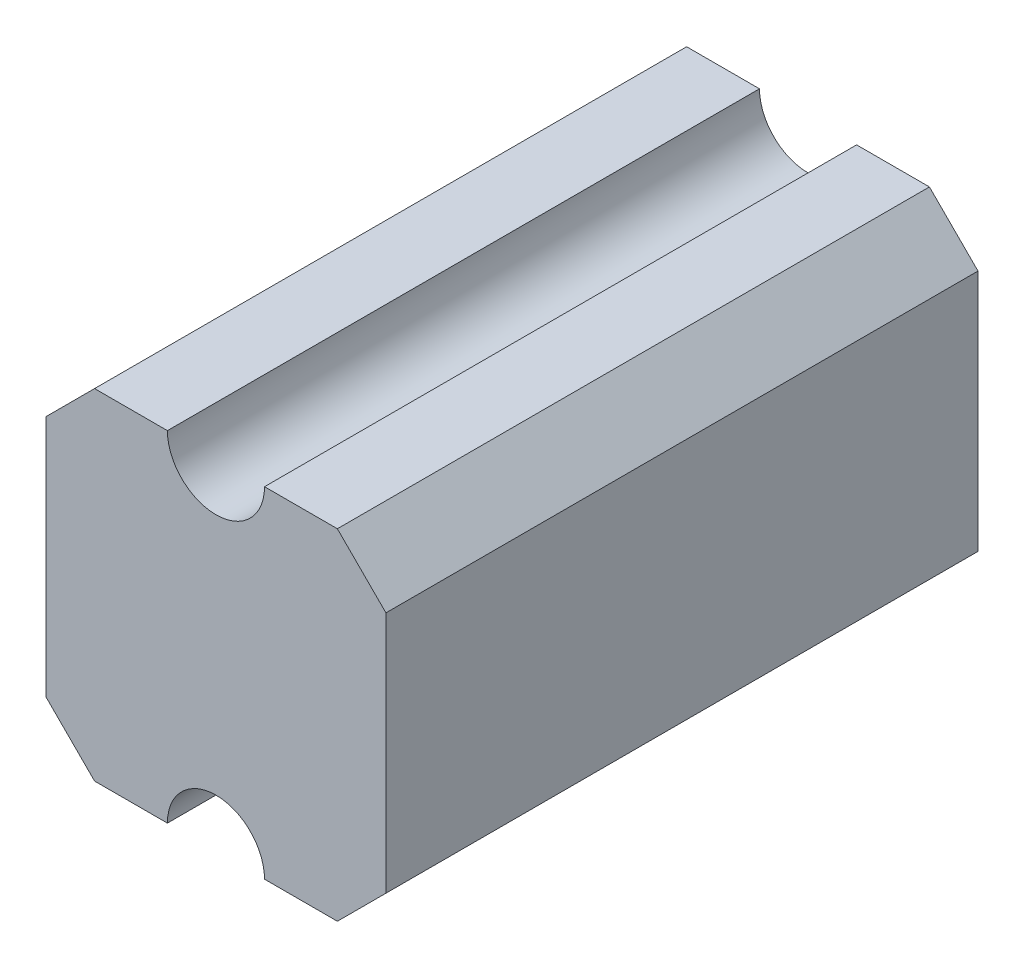
SolidWorks part; units mm, degrees
ref_plane "Front Plane" through (0, 0, 0) normal (0, 0, 1) x (1, 0, 0)
ref_plane "Top Plane" through (0, 0, 0) normal (0, 1, 0) x (1, 0, 0)
ref_plane "Right Plane" through (0, 0, 0) normal (1, 0, 0) x (0, 0, -1)
sketch3d "3DSketch1"
  line L2 (177.8, 103.1591, 1515.8003) -> (177.8, 458.7543, 1515.8003)
  line L3 (177.8, 458.7543, 1515.8003) -> (-177.8, 458.7543, 1515.8003)
  line L4 (-177.8, 458.7543, 1515.8003) -> (-177.8, 103.1591, 1515.8003)
  line L5 (-177.8, 103.1591, 1515.8003) -> (177.8, 103.1591, 1515.8003)
  line L8 (177.8, 50.7952, 937.9503) -> (234.95, 239.528, 988.7503)
  line L9 (234.95, 239.528, 988.7503) -> (234.95, 239.528, 753.8003)
  line L17 (-177.8, 50.7952, 937.9503) -> (-234.95, 239.528, 988.7503)
  line L18 (-234.95, 239.528, 988.7503) -> (-234.95, 239.528, 753.8003)
  line L26 (177.8, 50.7952, 753.8003) -> (304.8, 0, 0)
  line L27 (-177.8, 50.7952, 753.8003) -> (-304.8, 0, 0)
  line L29 (-234.95, 239.528, 753.8003) -> (-336.55, 241.3, -38.2182)
  line L32 (234.95, 239.528, 753.8003) -> (336.55, 241.3, -38.2182)
  line L41 (234.95, 241.3, -482.5997) -> (177.8, 50.7952, -482.5997) construction
  line L48 (-234.95, 241.3, -482.5997) -> (-177.8, 50.7952, -482.5997) construction
  line L71 (-336.55, 241.3, -38.2182) -> (336.55, 241.3, -38.2182)
  line L74 (177.8, 50.7952, 753.8003) -> (234.95, 239.528, 753.8003)
  line L75 (-177.8, 50.7952, 753.8003) -> (-234.95, 239.528, 753.8003)
  line L76 (-177.8, 50.7952, 937.9503) -> (177.8, 50.7952, 937.9503)
  line L78 (-234.95, 239.528, 753.8003) -> (-211.8982, 518.4742, 833.8369)
  line L80 (211.8982, 518.4742, 833.8369) -> (215.9, 531.628, 753.8003)
  line L83 (-215.9, 531.628, 753.8003) -> (-211.8982, 518.4742, 833.8369)
  line L84 (215.9, 531.628, 753.8003) -> (336.55, 241.3, -38.2182)
  line L85 (-215.9, 531.628, 753.8003) -> (-336.55, 241.3, -38.2182)
  line L94 (-215.9, 531.628, 753.8003) -> (215.9, 531.628, 753.8003)
  line L98 (-336.55, 241.3, -38.2182) -> (-251.3077, 21.3949, 317.5)
  line L104 (177.8, 50.7952, -482.5997) -> (-177.8, 50.7952, -482.5997) construction
  line L105 (336.55, 241.3, -38.2182) -> (234.95, 241.3, -380)
  line L106 (304.8, 0, 0) -> (238.125, 0, -380)
  line L107 (238.125, 0, -380) -> (177.8, 50.7952, -482.5997) construction
  line L109 (234.95, 241.3, -380) -> (238.125, 0, -380)
  line L112 (-336.55, 241.3, -38.2182) -> (-234.95, 241.3, -380)
  line L114 (-304.8, 0, 0) -> (-238.125, 0, -380)
  line L115 (-238.125, 0, -380) -> (-177.8, 50.7952, -482.5997) construction
  line L118 (-238.125, 0, -380) -> (-234.95, 241.3, -380)
  line L119 (304.8, 0, 0) -> (234.95, 241.3, -380)
  line L122 (-251.3077, 21.3949, 317.5) -> (-234.95, 239.528, 753.8003)
  line L123 (336.55, 241.3, -38.2182) -> (251.3077, 21.3949, 317.5)
  line L124 (251.3077, 21.3949, 317.5) -> (234.95, 239.528, 753.8003)
  line L125 (-177.8, 50.7952, 753.8003) -> (251.3077, 21.3949, 317.5)
  line L130 (251.3077, 21.3949, 317.5) -> (-251.3077, 21.3949, 317.5)
  line L133 (-336.55, 241.3, -38.2182) -> (336.55, 241.3, -38.2182) construction
  line L134 (-234.95, 239.528, 988.7503) -> (-211.8982, 518.4742, 833.8369)
  line L135 (234.95, 239.528, 988.7503) -> (211.8982, 518.4742, 833.8369)
  line L144 (211.8982, 518.4742, 833.8369) -> (234.95, 239.528, 753.8003)
  line L145 (0, 0, 0) -> (0, 201.59, 0) construction
  line L146 (-211.8982, 518.4742, 833.8369) -> (211.8982, 518.4742, 833.8369)
  line L162 (0, 53.4533, 0) -> (0, 104.2533, 0) construction
  line L164 (234.95, 241.3, -380) -> (177.8, 50.7952, -482.5997) construction
  line L166 (-234.95, 241.3, -482.5997) -> (-234.95, 241.3, -380) construction
  line L168 (336.55, 241.3, -38.2182) -> (268.0257, 127.0384, -200.0605)
  line L169 (268.0257, 127.0384, -200.0605) -> (238.125, 0, -380)
  line L170 (-304.8, 0, 0) -> (-234.95, 241.3, -380)
  line L172 (-177.8, 50.7952, 753.8003) -> (-234.95, 239.528, 988.7503)
  line L176 (234.95, 241.3, -380) -> (234.95, 241.3, -482.5997) construction
  line L177 (177.8, 50.7952, 753.8003) -> (0, 38.6132, 573.0201)
  line L178 (268.0257, 127.0384, -200.0605) -> (0, 127.0384, -200.0605) construction
  line L179 (-238.125, 0, -380) -> (-268.0257, 127.0384, -200.0605)
  line L183 (-177.8, 50.7952, -482.5997) -> (-234.95, 241.3, -380) construction
  line L186 (0, 127.0384, -200.0605) -> (-268.0257, 127.0384, -200.0605) construction
  line L193 (234.95, 239.528, 988.7503) -> (177.8, 50.7952, 753.8003)
  line L194 (-268.0257, 127.0384, -200.0605) -> (-336.55, 241.3, -38.2182)
  line L195 (304.8, 0, 0) -> (336.55, 241.3, -38.2182) construction
  line L196 (0, 38.6132, 573.0201) -> (-251.3077, 21.3949, 317.5)
  line L197 (-194.945, 50.7952, 753.8003) -> (194.945, 50.7952, 753.8003)
  line L198 (257.175, 0, -380) -> (-257.175, 0, -380)
  line L199 (-177.8, 50.7952, 937.9503) -> (177.8, 50.7952, 753.8003) construction
  line L200 (-177.8, 50.7952, 753.8003) -> (177.8, 50.7952, 937.9503)
  line L201 (-177.8, 50.7952, 937.9503) -> (0, 50.7952, 845.8753)
  line L202 (0, 50.7952, 845.8753) -> (177.8, 50.7952, 753.8003)
  line L203 (254, 241.3, -380) -> (-254, 241.3, -380)
  line L205 (320.675, 120.65, -19.1091) -> (320.675, 125.0494, 8.6674) construction
  dimension "D4" = 19.05
  dimension "D1" = 17.145
  dimension "D2" = 17.145
  dimension "D3" = 19.05
  dimension "D6" = 19.05
  dimension "D5" = 19.05
  dimension "D7" = 50.8
ref_plane "Plane2" through (177.8, 0, 0) normal (1, 0, 0) x (0, 0, -1)
sketch "Sketch5" plane through (177.8, 0, 0) normal (1, 0, 0) x (0, 0, -1)
  line L0 (-937.9503, 50.7952) -> (-1043.9312, 103.1591) construction
  line L1 (-1043.9312, 103.1591) -> (-1515.8003, 103.1591) construction
  point P0 (-1515.8003, 103.1591)
  point P2 (-937.9503, 50.7952)
  dimension "D1" = 52.3639
sketch3d "3DSketch4"
  line L0 (177.8, 50.7952, 937.9503) -> (177.8, 103.1591, 1043.9312)
  line L1 (177.8, 103.1591, 1043.9312) -> (177.8, 103.1591, 1515.8003)
  line L2 (-177.8, 103.1591, 1043.9312) -> (-177.8, 103.1591, 1515.8003)
  line L3 (-177.8, 50.7952, 937.9503) -> (-177.8, 103.1591, 1043.9312)
  line L4 (234.95, 239.528, 988.7503) -> (177.8, 103.1591, 1043.9312)
  line L5 (234.95, 239.528, 988.7503) -> (177.8, 458.7543, 1515.8003)
  line L6 (177.8, 458.7543, 1515.8003) -> (211.8982, 518.4742, 833.8369)
  line L7 (-211.8982, 518.4742, 833.8369) -> (-177.8, 458.7543, 1515.8003)
  line L8 (-177.8, 458.7543, 1515.8003) -> (-234.95, 239.528, 988.7503)
  line L9 (-234.95, 239.528, 988.7503) -> (-177.8, 103.1591, 1043.9312)
  line L10 (-177.8, 103.1591, 1043.9312) -> (177.8, 103.1591, 1043.9312)
  line L11 (-177.8, 50.7952, 937.9503) -> (177.8, 103.1591, 1043.9312)
  line L12 (-177.8, 103.1591, 1043.9312) -> (177.8, 50.7952, 937.9503)
  line L13 (177.8, 50.7952, 937.9503) -> (177.8, 50.7952, 753.8003)
  line L14 (-177.8, 50.7952, 937.9503) -> (-177.8, 50.7952, 753.8003)
ref_plane "Main Hoop Plane" through (0, 0, 0) normal (0, 0.1564, 0.9877) x (1, 0, 0)
sketch "Sketch7" plane through (0, 0, 0) normal (0, 0.1564, 0.9877) x (1, 0, 0)
  line L0 (-271.9714, 538.3394) -> (271.9714, 538.3394)
  line L1 (-334.5953, 259.4832) -> (-178.561, 954.2842)
  line L2 (304.8, 0) -> (-304.8, 0) construction
  line L3 (334.5953, 259.4832) -> (178.561, 954.2842)
  line L4 (0, 0) -> (0, 1084.4477) construction
  line L5 (302.6595, -15.875) -> (335.8611, 230.3644)
  line L6 (166.1209, 982.8477) -> (-166.1209, 982.8477) construction
  line L7 (-302.6595, -15.875) -> (-335.8611, 230.3644)
  line L8 (-143.9803, 1004.7664) -> (-45.9632, 1070.468)
  line L9 (45.9632, 1070.468) -> (143.9803, 1004.7664)
  line L10 (-302.6595, -15.875) -> (302.6595, -15.875) construction
  arc A0 (335.8611, 230.3644) -> (334.5953, 259.4832) centre (254.0514, 241.3952) ccw
  arc A1 (-334.5953, 259.4832) -> (-335.8611, 230.3644) centre (-254.0514, 241.3952) ccw
  arc A2 (-143.9803, 1004.7664) -> (-178.561, 954.2842) centre (-98.0171, 936.1961) ccw
  arc A3 (-45.9632, 1070.468) -> (45.9632, 1070.468) centre (0, 1001.8977) cw
  arc A4 (143.9803, 1004.7664) -> (178.561, 954.2842) centre (98.0171, 936.1961) cw
  point P2 (271.9714, 538.3394)
  point P5 (-271.9714, 538.3394)
  point P6 (0, 0)
  point P25 (0, 1084.4477)
  dimension "D1" = 165.1
  dimension "D2" = 82.55
  dimension "D3" = 82.55
  dimension "D4" = 332.2417
  dimension "D5" = 101.6
  dimension "D6" = 7.679
  dimension "D7" = 7.679
  dimension "D8" = 15.875
ref_plane "Plane4" through (0, 50.7952, 0) normal (0, 1, 0) x (1, 0, 0)
sketch "Sketch8" plane through (0, 50.7952, 0) normal (0, 1, 0) x (1, 0, 0)
  line L0 (0, 482.5997) -> (0, 1317.4595) construction
  line L1 (177.8, 482.5997) -> (-177.8, 482.5997) construction
  line L2 (-229.61, 803.9997) -> (229.61, 482.5997) construction
  line L3 (-229.61, 482.5997) -> (229.61, 482.5997)
  line L4 (-229.61, 482.5997) -> (-229.61, 803.9997)
  line L5 (-229.61, 803.9997) -> (229.61, 803.9997)
  line L6 (229.61, 482.5997) -> (229.61, 803.9997)
  point P9 (0, 643.2997)
  dimension "D1" = 321.4
  dimension "D2" = 459.22
sketch3d "3DSketch6"
  line L0 (238.125, 0, -380) -> (229.61, 50.7952, -482.5997)
  line L1 (-238.125, 0, -380) -> (-229.61, 50.7952, -482.5997)
  line L2 (229.61, 50.7952, -803.9997) -> (229.61, 364.0052, -803.9997)
  line L3 (-229.61, 50.7952, -803.9997) -> (229.61, 50.7952, -803.9997) construction
  line L4 (-229.61, 50.7952, -803.9997) -> (-229.61, 364.0052, -803.9997)
  line L5 (0, 50.7952, -643.2997) -> (-375.7156, 50.7952, -643.2997) construction
  line L6 (-229.61, 50.7952, -803.9997) -> (229.61, 50.7952, -482.5997) construction
  line L7 (229.61, 50.7952, -482.5997) -> (229.61, 364.0052, -482.5997)
  line L8 (-229.61, 50.7952, -482.5997) -> (-229.61, 364.0052, -482.5997)
  line L9 (229.61, 364.0052, -482.5997) -> (229.61, 364.0052, -803.9997)
  line L10 (-229.61, 364.0052, -803.9997) -> (229.61, 364.0052, -803.9997)
  line L11 (-229.61, 364.0052, -803.9997) -> (-229.61, 364.0052, -482.5997)
  line L12 (229.61, 364.0052, -482.5997) -> (234.95, 241.3, -380)
  line L13 (-234.95, 241.3, -380) -> (-229.61, 364.0052, -482.5997)
  line L14 (-234.95, 241.3, -380) -> (-229.61, 50.7952, -482.5997)
  line L15 (234.95, 241.3, -380) -> (229.61, 50.7952, -482.5997)
  line L17 (0, 50.7952, -482.5997) -> (229.61, 364.0052, -482.5997)
  line L18 (0, 50.7952, -482.5997) -> (-229.61, 364.0052, -482.5997)
  line L19 (-229.61, 50.7952, -803.9997) -> (229.61, 364.0052, -803.9997)
  line L20 (229.61, 50.7952, -803.9997) -> (-229.61, 364.0052, -803.9997)
  line L21 (229.61, 364.0052, -482.5997) -> (166.1209, 970.7472, -153.7513)
  line L23 (-166.1209, 970.7472, -153.7513) -> (-229.61, 364.0052, -482.5997)
  line L24 (166.1209, 970.7472, -153.7513) -> (-166.1209, 970.7472, -153.7513) construction
  arc A0 (143.9803, 992.3961, -157.1801) -> (178.561, 942.5354, -149.2829) centre (98.0171, 924.67, -146.4533) ccw construction
  arc A1 (-143.9803, 992.3961, -157.1801) -> (-178.561, 942.5354, -149.2829) centre (-98.0171, 924.67, -146.4533) ccw construction
  point P30 (98.0171, 911.7563, -227.987)
  point P38 (-98.0171, 937.5836, -64.9197)
  dimension "D1" = 313.21
  dimension "D2" = 313.21
sketch "Main Hoop Angle Check" plane through (0, 0, 0) normal (1, 0, 0) x (0, 0, -1)
  line L0 (482.5997, 364.0052) -> (153.7513, 970.7472) construction
  line L1 (0, 0) -> (169.645, 1071.0964) construction
  line L2 (482.5997, 364.0052) -> (153.7513, 970.7472)
  line L3 (0, 0) -> (169.645, 1071.0964)
  dimension "D1" = 37.457
ref_plane "front hoop plane" through (0, 0, 753.8003) normal (0, 0, 1) x (1, 0, 0)
sketch "Frront hoop" plane through (0, 0, 753.8003) normal (0, 0, 1) x (1, 0, 0)
  line L0 (176.7052, 31.7452) -> (228.7171, 203.51)
  line L1 (-0.0179, 531.628) -> (-0.0179, 576.078) construction
  line L2 (-176.7052, 31.7452) -> (-228.7171, 203.51)
  line L3 (-163.0801, 558.7261) -> (-15.8037, 574.3982)
  line L4 (163.0097, 558.7691) -> (15.7683, 574.4019)
  line L5 (-235.1226, 245.6706) -> (-236.8559, 476.0598)
  line L6 (235.1227, 245.6797) -> (236.8419, 476.0645)
  line L7 (0, -15.4366) -> (0, 246.7942) construction
  line L8 (182.4737, 50.7952) -> (-182.4737, 50.7952) construction
  line L9 (176.7052, 31.7452) -> (-176.7052, 31.7452) construction
  line L12 (-215.9, 531.628) -> (215.9, 531.628) construction
  arc A0 (-163.0801, 558.7261) -> (-236.8559, 476.0598) centre (-154.3494, 476.6805) ccw
  arc A1 (236.8419, 476.0645) -> (163.0097, 558.7691) centre (154.2942, 476.6805) ccw
  arc A2 (-15.8037, 574.3982) -> (15.7683, 574.4019) centre (0, 425.8847) cw
  arc A3 (-235.1226, 245.6706) -> (-228.7171, 203.51) centre (-85.7749, 246.7942) ccw
  arc A4 (235.1227, 245.6797) -> (228.7171, 203.51) centre (85.7749, 246.7942) cw
  dimension "D1" = 82.55
  dimension "D2" = 149.352
  dimension "D4" = 149.352
  dimension "D3" = 44.45
  dimension "D5" = 19.05
  dimension "D6" = 473.6978
  dimension "D7" = 525.2828
  dimension "D8" = 262.2308
  dimension "D9" = 235.1227
  dimension "D10" = 235.1227
  dimension "D11" = 470.2453
ref_plane "Footbox Template" through (0, 0, 1043.9312) normal (0, 0, 1) x (1, 0, 0)
sketch "Sketch11" plane through (0, 0, 1043.9312) normal (0, 0, 1) x (1, 0, 0)
  line L0 (-177.8, 458.7543) -> (177.8, 103.1591) construction
  line L1 (177.8, 458.7543) -> (-177.8, 103.1591) construction
  line L2 (0, 468.6567) -> (0, 118.6567) construction
  line L3 (125, 468.6567) -> (50, 468.6567)
  line L4 (-125, 468.6567) -> (-175, 418.6567)
  line L5 (-175, 418.6567) -> (-175, 168.6567)
  line L6 (-175, 168.6567) -> (-125, 118.6567)
  line L7 (-125, 118.6567) -> (-50, 118.6567)
  line L8 (175, 168.6567) -> (125, 118.6567)
  line L9 (175, 418.6567) -> (175, 168.6567)
  line L10 (125, 468.6567) -> (175, 418.6567)
  line L11 (-50, 468.6567) -> (-125, 468.6567)
  line L12 (50, 118.6567) -> (125, 118.6567)
  line L13 (-150, 443.6567) -> (150, 143.6567) construction
  line L14 (150, 443.6567) -> (-150, 143.6567) construction
  line L15 (0, 280.9567) -> (0, 293.6567) construction
  line L16 (0, 0) -> (0, 1071.0964) construction
  arc A0 (-50, 468.6567) -> (50, 468.6567) centre (0, 468.6567) ccw
  arc A1 (-50, 118.6567) -> (50, 118.6567) centre (0, 118.6567) cw
  point P30 (0, 293.6567)
  dimension "D4" = 50
  dimension "D1" = 350
  dimension "D2" = 350
  dimension "D3" = 50
  dimension "D5" = 424.2641
  dimension "D6" = 12.7
extrude "Cockpit Template" add sketch "Sketch11" along normal mid plane 609.6
ref_plane "Plane7" through (-229.61, 0, 0) normal (1, 0, 0) x (0, 0, -1)
sketch "Sketch12" plane through (-229.61, 0, 0) normal (1, 0, 0) x (0, 0, -1)
  line L0 (482.5997, 241.3) -> (482.5997, 50.7952) construction
  line L1 (482.5997, 50.7952) -> (482.5997, 364.0052) construction
  line B0 (482.5997, 50.7961) -> (803.9997, 50.7961) construction
  line B1 (803.9997, 50.7961) -> (803.9997, 364.0043) construction
  line B2 (803.9997, 364.0043) -> (482.5997, 364.0043) construction
  line B3 (482.5997, 364.0043) -> (482.5997, 50.7961) construction
  line B4 (482.5997, 50.7961) -> (803.9997, 364.0043) construction
  arc B5 (693.8038, 334.8108) -> (531.7068, 241.224) centre (659.2997, 207.4002) ccw
sketch_block_instance "Block3-1"
sketch_block "Block3"
sketch_block_instance "Block2-1"
sketch_block "Block2" parameters "D1"=12.7, "D2"=12.7, "D3"=12.7, "D4"=12.7, "D5"=12.7
